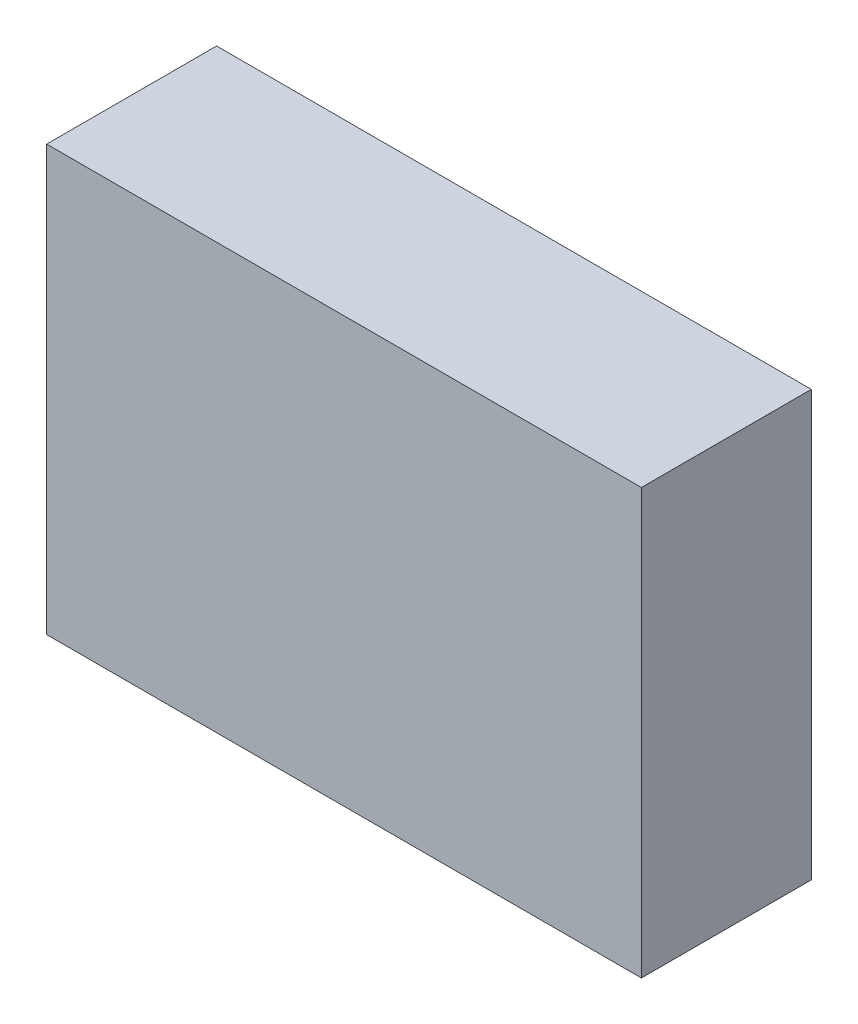
SolidWorks part; units mm, degrees
ref_plane "Спереди" through (0, 0, 0) normal (0, 0, 1) x (1, 0, 0)
ref_plane "Сверху" through (0, 0, 0) normal (0, 1, 0) x (1, 0, 0)
ref_plane "Справа" through (0, 0, 0) normal (1, 0, 0) x (0, 0, -1)
sketch "Эскиз1" plane through (0, 0, 0) normal (0, 0, 1) x (1, 0, 0)
  line L1 (0, 0) -> (70, 0)
  line L2 (0, 0) -> (0, 50)
  line L3 (0, 50) -> (70, 50)
  line L4 (70, 0) -> (70, 50)
  dimension "D1" = 50
  dimension "D2" = 70
extrude "Бобышка-Вытянуть1" add sketch "Эскиз1" along normal blind 20
